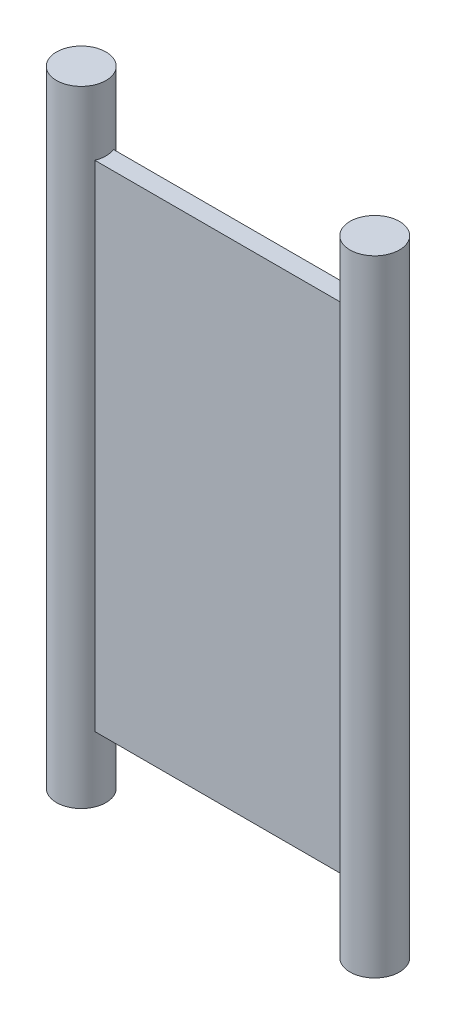
SolidWorks part; units mm, degrees
ref_plane "Front Plane" through (0, 0, 0) normal (0, 0, 1) x (1, 0, 0)
ref_plane "Top Plane" through (0, 0, 0) normal (0, 1, 0) x (1, 0, 0)
ref_plane "Right Plane" through (0, 0, 0) normal (1, 0, 0) x (0, 0, -1)
sketch "Sketch1" plane through (0, 0, 0) normal (0, 1, 0) x (1, 0, 0)
  line L1 (7.86, 0.5) -> (-7.86, 0.5)
  line L2 (7.86, 0.5) -> (7.86, -0.5)
  line L3 (7.86, -0.5) -> (-7.86, -0.5)
  line L4 (-7.86, 0.5) -> (-7.86, -0.5)
  line L5 (7.86, 0.5) -> (-7.86, -0.5) construction
  line L6 (7.86, -0.5) -> (-7.86, 0.5) construction
  point P0 (0, 0)
  dimension "D1" = 15.72
  dimension "D3" = 1
extrude "Boss-Extrude1" add sketch "Sketch1" along normal blind 26.5
ref_plane "Plane1" through (0, 13.25, 0) normal (0, 1, 0) x (1, 0, 0)
sketch "Sketch2" plane through (0, 13.25, 0) normal (0, 1, 0) x (1, 0, 0)
  line L0 (7.86, -0.5) -> (7.86, 0.5) construction
  line L1 (-7.86, 0.5) -> (-7.86, -0.5) construction
  line L2 (7.86, -0.5) -> (7.86, 0.5) construction
  line L3 (-7.86, 0.5) -> (-7.86, -0.5) construction
  circle A0 centre (-7.86, 0) radius 1.325
  circle A1 centre (7.86, 0) radius 1.325
  dimension "D1" = 2.65
extrude "Boss-Extrude2" add sketch "Sketch2" along normal mid plane 33.5
